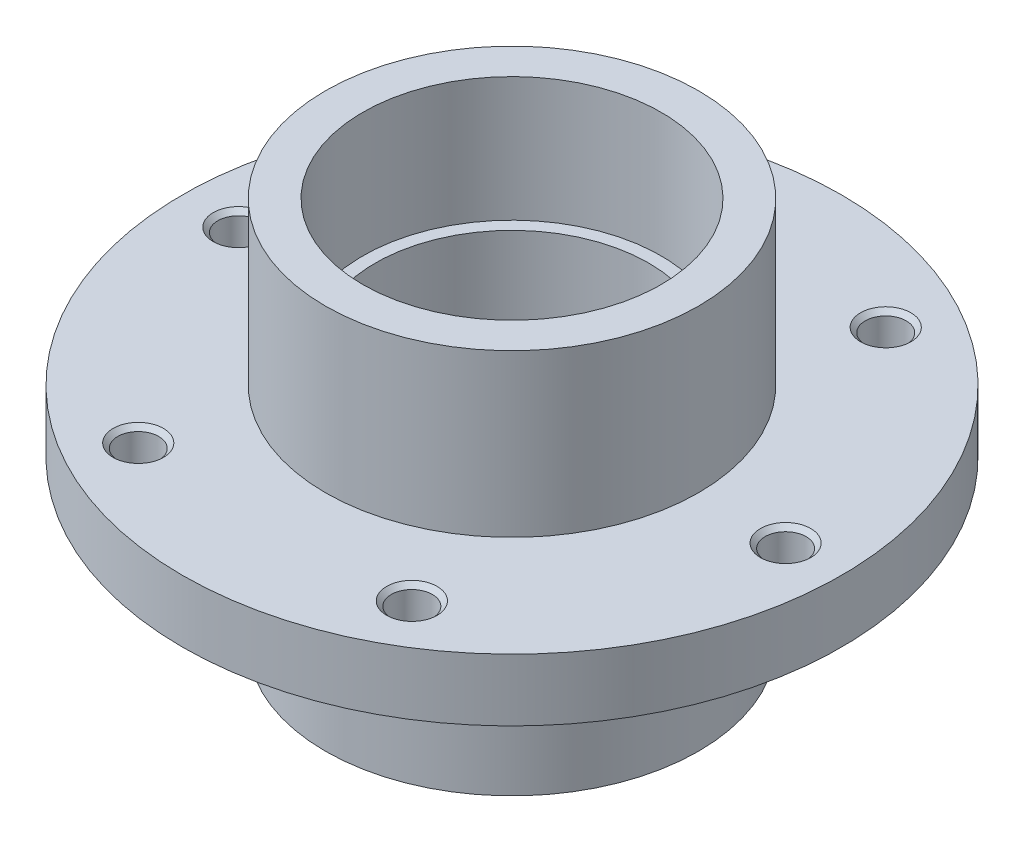
SolidWorks part; units mm, degrees
material "1060 合金"
ref_plane "前视基准面" through (0, 0, 0) normal (0, 0, 1) x (1, 0, 0)
ref_plane "上视基准面" through (0, 0, 0) normal (0, 1, 0) x (1, 0, 0)
ref_plane "右视基准面" through (0, 0, 0) normal (1, 0, 0) x (0, 0, -1)
sketch "草图1" plane through (0, 0, 0) normal (0, 1, 0) x (1, 0, 0)
  circle A0 centre (0, 0) radius 26.5
  dimension "D1" = 53
extrude "凸台-拉伸2" add sketch "草图1" along normal blind 5
sketch "草图3" plane through (0, 5, 0) normal (0, 1, 0) x (1, 0, 0)
  circle A0 centre (0, 0) radius 15
  dimension "D1" = 30
extrude "凸台-拉伸3" add sketch "草图3" along normal blind 13
sketch "草图4" plane through (0, 0, 0) normal (0, -1, 0) x (1, 0, 0)
  circle A0 centre (0, 0) radius 15
  dimension "D1" = 30
extrude "凸台-拉伸4" add sketch "草图4" along normal blind 13
hole_wizard "M4 螺纹孔1" positions "3D草图1" profile "草图6" tap size "M4" standard "GB"
sketch3d "3D草图1"
  line L2 (0, 0, 0) -> (27.585, 0, 0) construction
  line L4 (22, 0, 0) -> (22, 8.9561, 0) construction
  point P0 (22, 5, 0)
  dimension "D1" = 22
sketch "草图6" plane through (22, 5, 0) normal (1, 0, 0) x (0, 0, 1)
  line L0 (0, 0) -> (0, 5.9904)
  line L1 (0, 5.9904) -> (1.65, 4.999)
  line L2 (1.65, 4.999) -> (1.65, 0.375)
  line L3 (1.65, 0.375) -> (2.025, 0)
  line L5 (2.025, 0) -> (0, 0)
  line L6 (-1.65, 0.375) -> (-2.025, 0) construction
  line L10 (0, 5.9904) -> (-1.65, 4.999) construction
  line L11 (0, -6.35) -> (0, 107.95) construction
  dimension "螺纹孔钻头直径" = 3.3
  dimension "螺纹孔钻头深度" = 4.999
  dimension "近端锥形沉头孔直径" = 4.05
  dimension "近端锥形沉头孔角度" = 90
  dimension "导头角度" = 118
cosmetic thread "孔螺蚊线1" parameters "D1"=8, "D2"=4
pattern_circular "阵列(圆周)1" count 6 over 360 about axis through (0, 0, 0) along (0, 1, 0) of "M4 螺纹孔1"
cosmetic thread "孔螺蚊线2" parameters "D1"=8, "D2"=4
cosmetic thread "孔螺蚊线3" parameters "D1"=8, "D2"=4
cosmetic thread "孔螺蚊线4" parameters "D1"=8, "D2"=4
cosmetic thread "孔螺蚊线5" parameters "D1"=8, "D2"=4
cosmetic thread "孔螺蚊线6" parameters "D1"=8, "D2"=4
sketch "草图7" plane through (0, 18, 0) normal (0, 1, 0) x (1, 0, 0)
  circle A0 centre (0, 0) radius 11
  dimension "D1" = 22
extrude "切除-拉伸1" cut sketch "草图7" against normal up to surface (31 mm away) up to face at (0, -13, -15)
ref_plane "基准面1" through (0, 2.5, 0) normal (0, 1, 0) x (1, 0, 0)
sketch "草图8" plane through (0, 18, 0) normal (0, 1, 0) x (1, 0, 0)
  circle A0 centre (0, 0) radius 12
  dimension "D1" = 24
extrude "切除-拉伸2" cut sketch "草图8" against normal blind 10
mirror "镜向1" about plane through (0, 2.5, 0) normal (0, 1, 0) of "切除-拉伸2"
